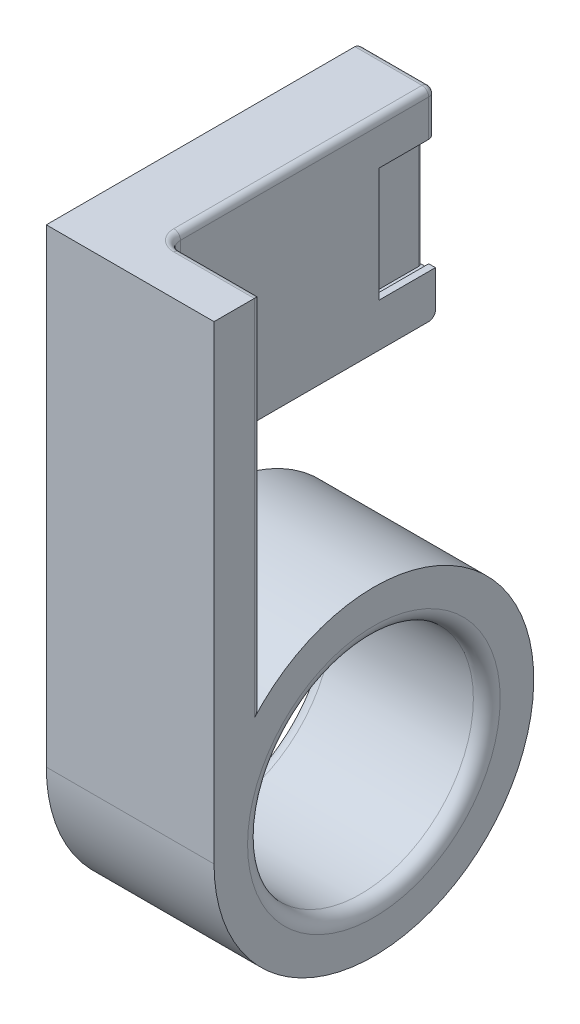
SolidWorks part; units mm, degrees
ref_plane "Front Plane" through (0, 0, 0) normal (0, 0, 1) x (1, 0, 0)
ref_plane "Top Plane" through (0, 0, 0) normal (0, 1, 0) x (1, 0, 0)
ref_plane "Right Plane" through (0, 0, 0) normal (1, 0, 0) x (0, 0, -1)
sketch "Sketch1" plane through (0, 0, 0) normal (1, 0, 0) x (0, 0, -1)
  circle A0 centre (0, 0) radius 16.8275
  circle A1 centre (0, 0) radius 23.8275
  dimension "D1" = 33.655
  dimension "D2" = 7
extrude "Boss-Extrude1" add sketch "Sketch1" along normal blind 25 contours A1 | A0
sketch "Sketch2" plane through (0, 0, 0) normal (0, 1, 0) x (1, 0, 0)
  line L0 (25, -23.8275) -> (25, 23.8275) construction
  line L1 (0, -23.8275) -> (25, -23.8275)
  line L2 (0, -23.8275) -> (0, -16.8275)
  line L3 (0, -16.8275) -> (25, -16.8275)
  line L4 (25, -23.8275) -> (25, -16.8275)
  line L5 (25, -16.8275) -> (25, 16.8275) construction
extrude "Boss-Extrude2" add sketch "Sketch2" along normal blind 70
sketch "Sketch3" plane through (0, 0, 16.8275) normal (0, 0, -1) x (-1, 0, 0)
  line L1 (0, 70) -> (-11, 70)
  line L2 (0, 70) -> (0, 40)
  line L3 (0, 40) -> (-11, 40)
  line L4 (-11, 70) -> (-11, 40)
  dimension "D1" = 11
  dimension "D2" = 30
extrude "Boss-Extrude3" add sketch "Sketch3" along normal blind 40
sketch "Sketch4" plane through (11, 0, 0) normal (1, 0, 0) x (0, 0, -1)
  line L0 (23.1725, 70) -> (23.1725, 40) construction
  line L1 (23.1725, 55) -> (-16.8275, 55)
  line L2 (-16.8275, 70) -> (-16.8275, 40) construction
  line L4 (14.7725, 63.525) -> (23.1725, 63.525)
  line L5 (14.7725, 63.525) -> (14.7725, 46.475)
  line L6 (14.7725, 46.475) -> (23.1725, 46.475)
  line L7 (23.1725, 63.525) -> (23.1725, 46.475)
  line L8 (14.7725, 63.525) -> (23.1725, 46.475) construction
  line L9 (14.7725, 46.475) -> (23.1725, 63.525) construction
  point P8 (18.9725, 55)
  line M8 (23.1725, 40) -> (23.1725, 70)
  dimension "D1" = 17.05
  dimension "D2" = 8.4
extrude "Cut-Extrude1" cut sketch "Sketch4" against normal blind 1 contours L5 L6 L1 M8 | L4 L5 L1 M8
sketch "Sketch5" plane through (10, 0, 0) normal (1, 0, 0) x (0, 0, -1)
  line L0 (23.1725, 63.525) -> (23.1725, 46.475) construction
  line L1 (23.1725, 55) -> (14.7725, 55) construction
  line L2 (14.7725, 63.525) -> (14.7725, 46.475) construction
  line L4 (14.1725, 64.125) -> (23.1725, 64.125)
  line L5 (14.1725, 64.125) -> (14.1725, 45.875)
  line L6 (14.1725, 45.875) -> (23.1725, 45.875)
  line L7 (23.1725, 64.125) -> (23.1725, 45.875)
  line L8 (14.1725, 64.125) -> (23.1725, 45.875) construction
  line L9 (14.1725, 45.875) -> (23.1725, 64.125) construction
  point P8 (18.6725, 55)
  dimension "D1" = 18.25
  dimension "D2" = 9
extrude "Cut-Extrude2" cut sketch "Sketch5" against normal blind 1
fillet "Fillet1" radius 0.5 1 edges at (9, 55, -23.1725)
fillet "Fillet2" radius 1 3 edges at (5.5, 40, -23.1725) (0, 55, -23.1725) (5.5, 70, -23.1725)
fillet "Fillet3" radius 2 2 edges at (25, 0, -16.8275) (0, 0, -16.8275)
fillet "Fillet4" radius 2 1 edges at (11, 55, 16.8275)
fillet "Fillet6" radius 1 6 edges at (11, 66.2625, -23.1725) (11, 69.7071, -22.8796) (11, 70, -3.6725) (11.5858, 70, 16.2417) (19, 70, 16.8275) (25, 43.4348, 16.8275)
